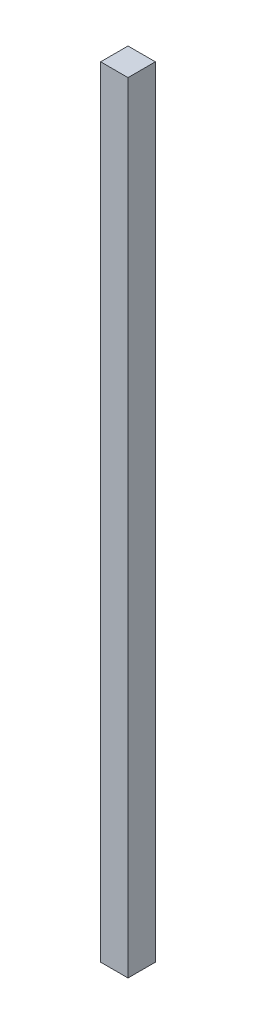
SolidWorks part; units mm, degrees
ref_plane "Спереди" through (0, 0, 0) normal (0, 0, 1) x (1, 0, 0)
ref_plane "Сверху" through (0, 0, 0) normal (0, 1, 0) x (1, 0, 0)
ref_plane "Справа" through (0, 0, 0) normal (1, 0, 0) x (0, 0, -1)
other "Configuration Table"
sketch "Эскиз1" plane through (0, 0, 0) normal (0, 1, 0) x (1, 0, 0)
  line L1 (25, 25) -> (-25, 25)
  line L2 (25, 25) -> (25, -25)
  line L3 (25, -25) -> (-25, -25)
  line L4 (-25, 25) -> (-25, -25)
  line L5 (25, 25) -> (-25, -25) construction
  line L6 (25, -25) -> (-25, 25) construction
  point P0 (0, 0)
extrude "Бобышка-Вытянуть1" add sketch "Эскиз1" along normal blind 1425
sketch "Эскиз2" plane through (0, 0, 0) normal (0, -1, 0) x (1, 0, 0)
  circle A0 centre (0, 0) radius 5
extrude "Вырез-Вытянуть1" cut sketch "Эскиз2" against normal blind 50
